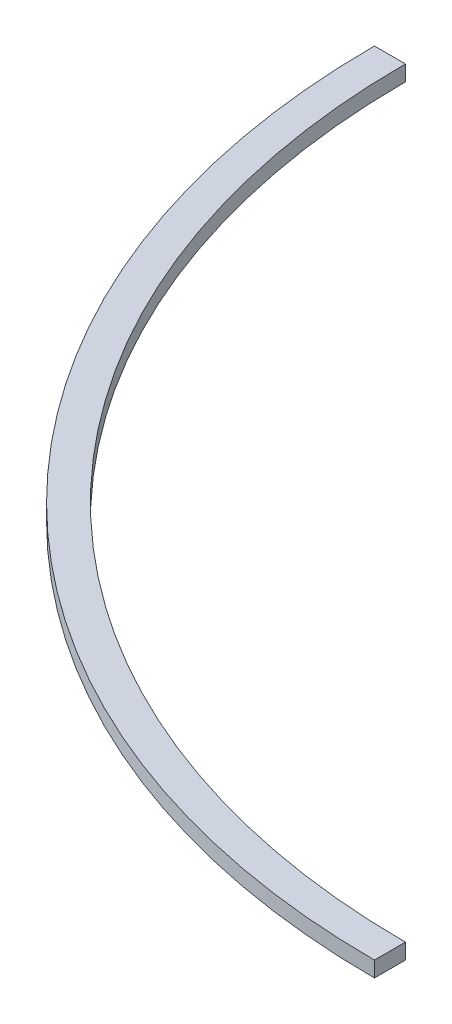
SolidWorks part; units mm, degrees
ref_plane "Front Plane" through (0, 0, 0) normal (0, 0, 1) x (1, 0, 0)
ref_plane "Top Plane" through (0, 0, 0) normal (0, 1, 0) x (1, 0, 0)
ref_plane "Right Plane" through (0, 0, 0) normal (1, 0, 0) x (0, 0, -1)
sketch "Sketch1" plane through (0, 0, 0) normal (0, 1, 0) x (1, 0, 0)
  line L0 (0, 0) -> (-510, 0)
  line L1 (0, 0) -> (0, -510)
  circle A0 centre (0, 0) radius 500 construction
  circle A1 centre (0, 0) radius 510
  circle A2 centre (0, 0) radius 490
  point P7 (0, 0)
  point P10 (0, 0)
  dimension "D1" = 1000
  dimension "D2" = 10
  dimension "D3" = 10
extrude "Boss-Extrude1" add sketch "Sketch1" along normal blind 10 contours A2 L0 A1 L1
